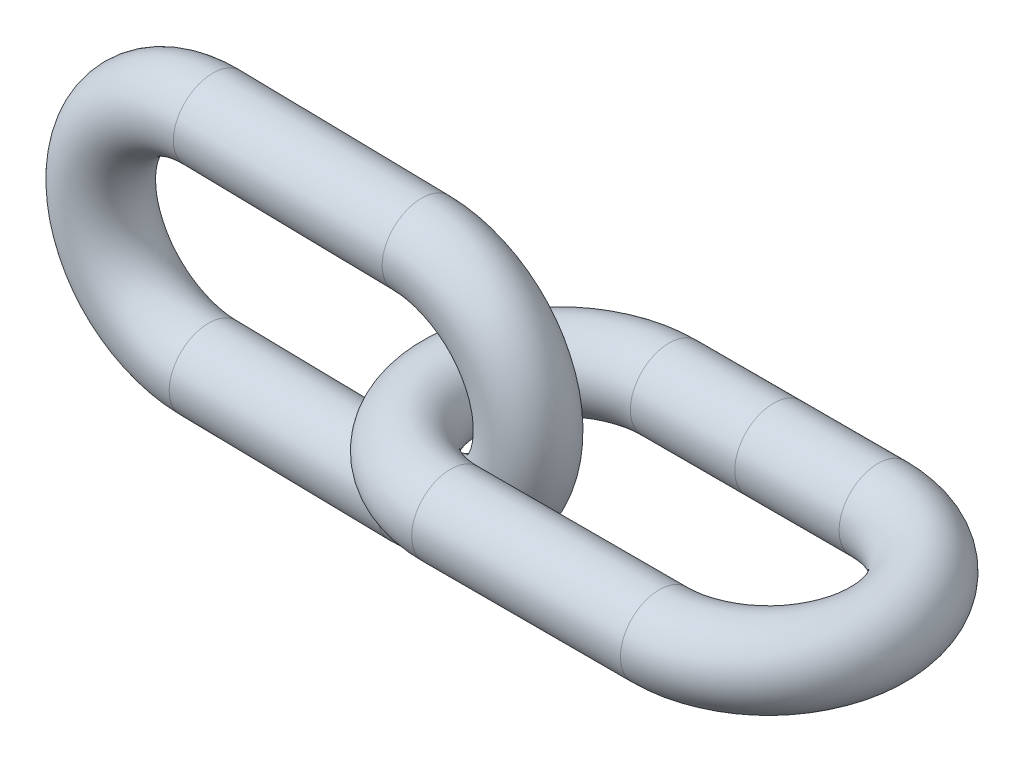
SolidWorks part; units mm, degrees
ref_plane "Front Plane" through (0, 0, 0) normal (0, 0, 1) x (1, 0, 0)
ref_plane "Top Plane" through (0, 0, 0) normal (0, 1, 0) x (1, 0, 0)
ref_plane "Right Plane" through (0, 0, 0) normal (1, 0, 0) x (0, 0, -1)
sketch "Sketch1" plane through (0, 0, 0) normal (0, 1, 0) x (1, 0, 0)
  line L0 (9.398, 9.8425) -> (-9.398, 9.8425)
  line L1 (-9.398, -9.8425) -> (9.398, -9.8425)
  line L2 (9.398, 0) -> (-9.398, 0) construction
  line L3 (9.398, 6.35) -> (-9.398, 6.35) construction
  line L4 (-9.398, -6.35) -> (9.398, -6.35) construction
  arc A0 (-9.398, 9.8425) -> (-9.398, -9.8425) centre (-9.398, 0) ccw
  arc A1 (9.398, -9.8425) -> (9.398, 9.8425) centre (9.398, 0) ccw
  arc A2 (9.398, -6.35) -> (9.398, 6.35) centre (9.398, 0) ccw construction
  arc A3 (-9.398, 6.35) -> (-9.398, -6.35) centre (-9.398, 0) ccw construction
  point P13 (-15.748, 0)
  point P14 (15.748, 0)
  dimension "D1" = 31.496
  dimension "D4" = 12.7
  dimension "D2" = 38.481
  dimension "D3" = 3.4925
sketch "Sketch2" plane through (0, 0, 0) normal (1, 0, 0) x (0, 0, -1)
  circle A0 centre (9.8425, 0) radius 3.4925
  dimension "D1" = 6.985
sweep "Sweep1" add profiles "Sketch2" path "Sketch1"
sketch "Sketch3" plane through (0, 0, 0) normal (0, 0, 1) x (1, 0, 0)
  line L0 (1310.64, 521.4198) -> (-1310.64, 521.4198) construction
  line L1 (0, 521.4198) -> (0, 0) construction
  spline S0 degree 2 poles (-1528.9591, 709.598) (0, -709.598) (1528.9591, 709.598) knots 0 0 0 1 1 1 construction
  spline S1 degree 2 poles (-1310.64, 521.4198) (0, -521.4198) (1310.64, 521.4198) knots 0.071395 0.071395 0.071395 0.928605 0.928605 0.928605
  point P0 (0, 0)
  dimension "D1" = 2621.28
  dimension "D2" = 521.4198
sketch "Sketch5" plane through (0, 0, 0) normal (0, 0, 1) x (1, 0, 0)
  line L0 (-21.906, 9.9889) -> (-40.6986, 10.3481)
  line L1 (-41.0749, -9.3333) -> (-22.2823, -9.6925)
  line L2 (-21.9728, 6.497) -> (-40.7653, 6.8563) construction
  line L3 (-41.0081, -5.8414) -> (-22.2155, -6.2007) construction
  arc A0 (-40.6986, 10.3481) -> (-41.0749, -9.3333) centre (-40.8867, 0.5074) ccw
  arc A1 (-22.2823, -9.6925) -> (-21.906, 9.9889) centre (-22.0942, 0.1482) ccw
  circle A2 centre (-19.2405, 0) radius 3.4925
  arc A3 (-22.2155, -6.2007) -> (-21.9728, 6.497) centre (-22.0942, 0.1482) ccw construction
  arc A4 (-40.7653, 6.8563) -> (-41.0081, -5.8414) centre (-40.8867, 0.5074) ccw construction
  arc A5 (-40.6986, 10.3481) -> (-41.0749, -9.3333) centre (-40.8867, 0.5074) ccw construction
  parabola Q5 (-1310.64, 521.4198) -> (1310.64, 521.4198) focus (0, 823.6057) apex (0, 0) construction
  parabola Q17 (-1310.64, 521.4198) -> (1310.64, 521.4198) focus (0, 823.6057) apex (0, 0) construction
  point P5 (-47.2356, 0.6288)
  point P6 (-19.2405, 0)
  point P20 (-15.7453, 0.0268)
  dimension "D3" = 6.985
  dimension "D1" = 31.496
  dimension "D2" = 12.7
  dimension "D5" = 3.4925
ref_plane "Plane1" through (-21.906, 9.9889, 0) normal (-0.9998, 0.0191, 0) x (0, 0, 1)
sketch "Sketch6" plane through (-21.906, 9.9889, 0) normal (-0.9998, 0.0191, 0) x (0, 0, 1)
  circle A0 centre (0, 0) radius 3.4925
  dimension "D1" = 6.985
sweep "Sweep2" add profiles "Sketch6" path "Sketch5"
